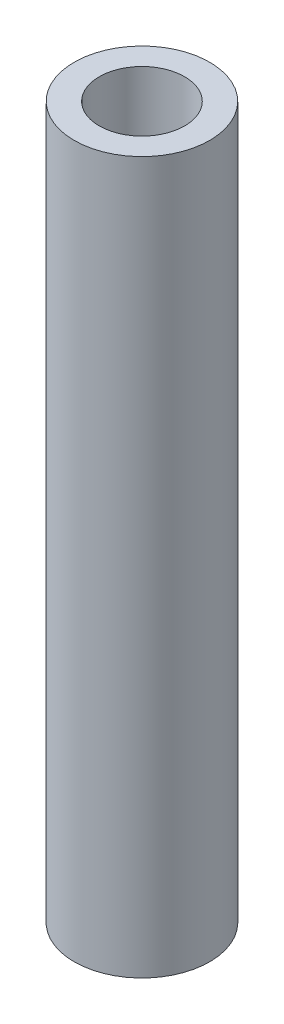
SolidWorks part; units mm, degrees
material "6061 Alloy"
ref_plane "X-Y Datum" through (0, 0, 0) normal (0, 0, 1) x (1, 0, 0)
ref_plane "X-Z Datum" through (0, 0, 0) normal (0, 1, 0) x (1, 0, 0)
ref_plane "Y-Z Datum" through (0, 0, 0) normal (1, 0, 0) x (0, 0, -1)
sketch "Sketch1" plane through (0, 0, 0) normal (0, 1, 0) x (1, 0, 0)
  circle A0 centre (0, 0) radius 3.175
  circle A1 centre (0, 0) radius 2
  dimension "D1" = 6.35
  dimension "D2" = 4
extrude "Boss-Extrude1" add sketch "Sketch1" against normal blind 33.3375
